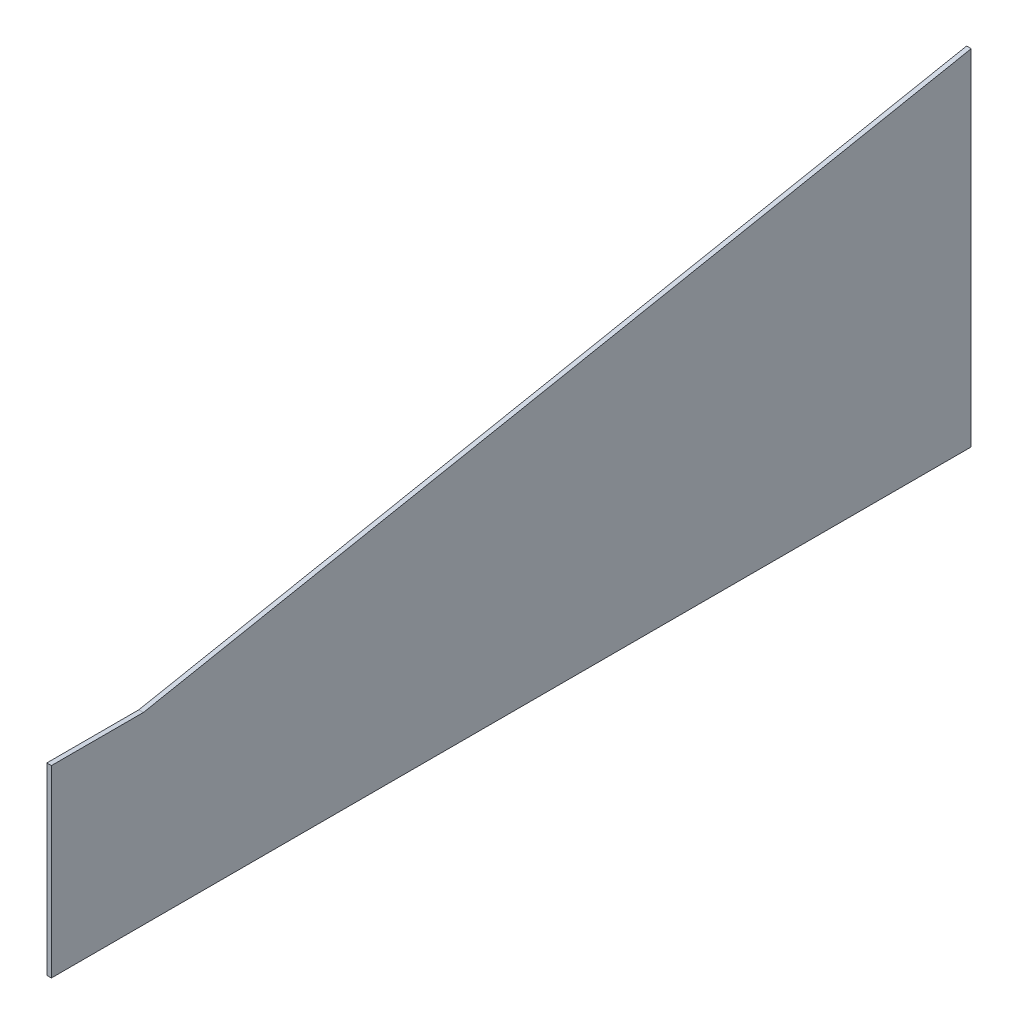
SolidWorks part; units mm, degrees
ref_plane "Front Plane" through (0, 0, 0) normal (0, 0, 1) x (1, 0, 0)
ref_plane "Top Plane" through (0, 0, 0) normal (0, 1, 0) x (1, 0, 0)
ref_plane "Right Plane" through (0, 0, 0) normal (1, 0, 0) x (0, 0, -1)
sketch "Sketch1" plane through (0, 0, 0) normal (1, 0, 0) x (0, 0, -1)
  line L0 (-800, 300) -> (1000, 650)
  line L3 (-1000, -100) -> (1000, -100)
  line L4 (1000, 100) -> (1000, -100)
  line L6 (-1000, -100) -> (-1000, 300)
  line L10 (1000, 100) -> (1000, 650)
  line L14 (1000, 100) -> (1000, 300)
  line L15 (-800, 300) -> (-1000, 300)
  point P0 (0, 0)
  dimension "D1" = 750
  dimension "D2" = 2000
extrude "Boss-Extrude1" add sketch "Sketch1" along normal blind 10
